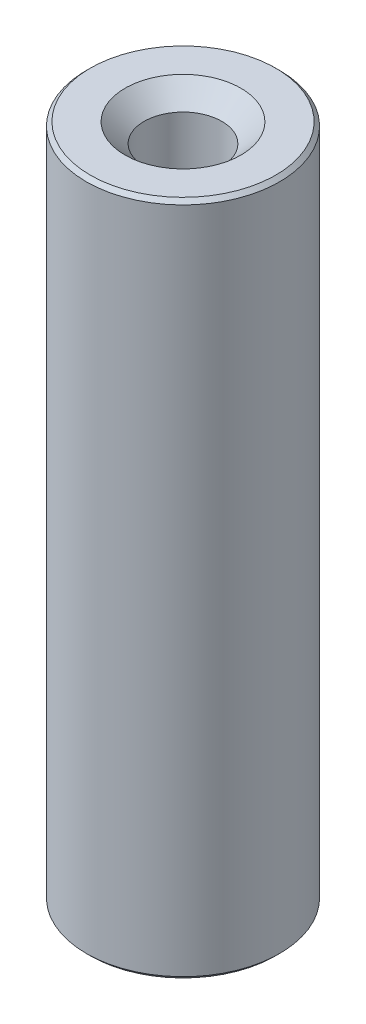
SolidWorks part; units mm, degrees
material "Plain Carbon Steel"
ref_plane "Front Plane" through (0, 0, 0) normal (0, 0, 1) x (1, 0, 0)
ref_plane "Top Plane" through (0, 0, 0) normal (0, 1, 0) x (1, 0, 0)
ref_plane "Right Plane" through (0, 0, 0) normal (1, 0, 0) x (0, 0, -1)
sketch "Sketch1" plane through (0, 0, 0) normal (0, 1, 0) x (1, 0, 0)
  circle A0 centre (0, 0) radius 6.35
  dimension "D1" = 12.7
extrude "Boss-Extrude1" add sketch "Sketch1" along normal blind 44.45
hole_wizard "1/4-20 Tapped Hole1" positions "Sketch2" profile "Sketch3" tap size "1/4-20" standard "ANSI Inch" end condition through all
sketch "Sketch2" plane through (0, 44.45, 0) normal (0, 1, 0) x (1, 0, 0)
  point P0 (0, 0)
sketch "Sketch3" plane through (0, 44.45, 0) normal (1, 0, 0) x (0, 0, 1)
  line L0 (0, 0) -> (0, 44.45)
  line L1 (0, 44.45) -> (3.81, 44.45)
  line L2 (2.5527, 43.1927) -> (2.5527, 1.2573)
  line L3 (2.5527, 1.2573) -> (3.81, 0)
  line L5 (3.81, 0) -> (0, 0)
  line L6 (-2.5527, 1.2573) -> (-3.81, 0) construction
  line L7 (3.81, 44.45) -> (2.5527, 43.1927)
  line L8 (-3.81, 44.45) -> (-2.5527, 43.1927) construction
  line L11 (0, -6.35) -> (0, 107.95) construction
  dimension "Thru Tap Drill Dia." = 5.1054
  dimension "Thru Tap Drill Depth" = 44.45
  dimension "Near C'Sink Dia." = 7.62
  dimension "Near C'Sink Angle" = 90
  dimension "Far C'Sink Dia." = 7.62
  dimension "Far C'Sink Angle" = 90
cosmetic thread "Hole Thread1" parameters "D2"=6.35
sketch "Sketch4" plane through (0, 44.45, 0) normal (0, 1, 0) x (1, 0, 0)
  line L0 (0, 0) -> (0, -25) construction
  circle A0 centre (0, -25) radius 20
  dimension "D1" = 25
  dimension "D2" = 40
extrude "Cut-Extrude1" [suppressed] cut sketch "Sketch4" against normal blind 19.05
chamfer "Chamfer1" distance 0.254 angle 45 2 edges at (0, 0, 6.35) (0, 44.45, 6.35)
